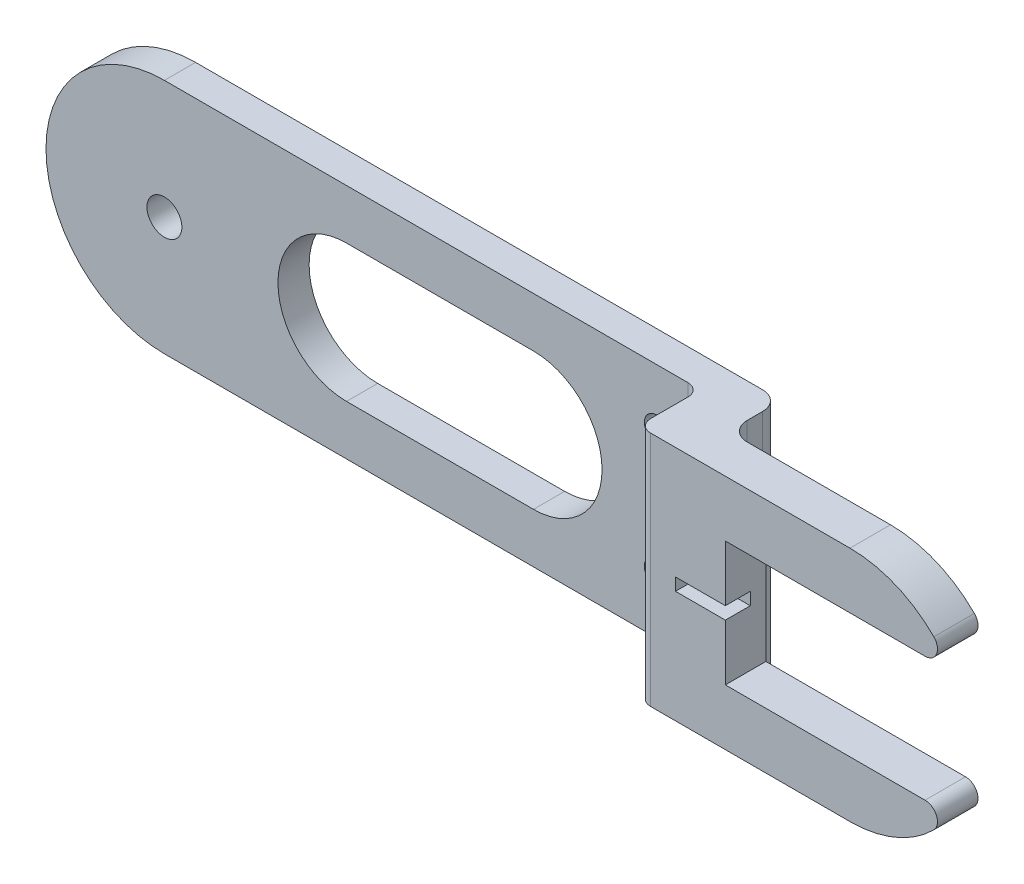
SolidWorks part; units mm, degrees
ref_plane "Front Plane" through (0, 0, 0) normal (0, 0, 1) x (1, 0, 0)
ref_plane "Top Plane" through (0, 0, 0) normal (0, 1, 0) x (1, 0, 0)
ref_plane "Right Plane" through (0, 0, 0) normal (1, 0, 0) x (0, 0, -1)
sketch "Sketch1" plane through (0, 0, 0) normal (0, 0, 1) x (1, 0, 0)
  line L0 (0, 0) -> (120, 0) construction
  line L1 (0, 19) -> (120, 19)
  line L2 (0, -19) -> (120, -19)
  line L3 (29.2177, 0) -> (59.2177, 0) construction
  line L4 (29.2177, 11) -> (59.2177, 11)
  line L5 (29.2177, -11) -> (59.2177, -11)
  line L7 (100, -10) -> (136.1555, -10)
  line L8 (100, -10) -> (100, 10)
  line L9 (100, 10) -> (136.1555, 10)
  line L11 (100, -10) -> (140, 10) construction
  line L12 (100, 10) -> (140, -10) construction
  circle A0 centre (0, 0) radius 2.8
  arc A1 (0, 19) -> (0, -19) centre (0, 0) ccw
  arc A2 (120, -19) -> (136.1555, -10) centre (120, 0) ccw
  arc A3 (29.2177, 11) -> (29.2177, -11) centre (29.2177, 0) ccw
  arc A4 (59.2177, -11) -> (59.2177, 11) centre (59.2177, 0) ccw
  arc A5 (136.1555, 10) -> (120, 19) centre (120, 0) ccw
  point P8 (44.2177, 0)
  point P17 (120, 0)
  dimension "D1" = 38
  dimension "D2" = 5.6
  dimension "D4" = 38
  dimension "D3" = 120
  dimension "D5" = 30
  dimension "D6" = 8
  dimension "D7" = 20
  dimension "D8" = 40
extrude "Boss-Extrude1" add sketch "Sketch1" along normal blind 5
fillet "Fillet1" radius 2 2 edges at (136.1555, 10, 2.5) (136.1555, -10, 2.5)
sketch "Sketch2" plane through (0, 0, 5) normal (0, 0, 1) x (1, 0, 0)
  line L0 (86, 19) -> (86, -19)
  line L1 (120, 19) -> (0, 19) construction
  line L2 (0, -19) -> (120, -19) construction
  line L3 (100, -10) -> (100, 10) construction
  line L4 (120, 19) -> (86, 19)
  line L6 (86, -19) -> (120, -19)
  line L7 (132.0416, -10) -> (100, -10) construction
  line L8 (132.0416, -10) -> (100, -10)
  line L9 (100, -10) -> (100, 10)
  line L10 (100, 10) -> (132.0416, 10) construction
  line L11 (100, 10) -> (132.0416, 10)
  arc A0 (133.4583, 13.4118) -> (120, 19) centre (120, 0) ccw construction
  arc A1 (133.4583, 13.4118) -> (120, 19) centre (120, 0) ccw
  arc A2 (120, -19) -> (133.4583, -13.4118) centre (120, 0) ccw construction
  arc A3 (120, -19) -> (133.4583, -13.4118) centre (120, 0) ccw
  arc A4 (133.4583, -13.4118) -> (132.0416, -10) centre (132.0416, -12) ccw construction
  arc A5 (133.4583, -13.4118) -> (132.0416, -10) centre (132.0416, -12) ccw
  arc A6 (132.0416, 10) -> (133.4583, 13.4118) centre (132.0416, 12) ccw construction
  arc A7 (132.0416, 10) -> (133.4583, 13.4118) centre (132.0416, 12) ccw
  point P8 (100, 0)
  dimension "D1" = 14
extrude "Boss-Extrude2" add sketch "Sketch2" along normal blind 10
fillet "Fillet2" radius 2 2 edges at (86, 0, 15) (86, 0, 5)
sketch "Sketch3" plane through (0, 0, 15) normal (0, 0, 1) x (1, 0, 0)
  line L0 (100, 0) -> (88, 0) construction
  line L1 (100, -10) -> (100, 10) construction
  line L2 (88, 19) -> (88, -19) construction
  line L3 (100, 1) -> (92, 1)
  line L4 (100, -1) -> (92, -1)
  line L5 (100, 1) -> (100, -1)
  line L6 (92, 1) -> (92, -1)
  line L8 (100, 1) -> (88, 1) construction
  line L9 (100, -1) -> (88, -1) construction
  dimension "D3" = 4
  dimension "D1" = 1
  dimension "D2" = 1
extrude "Cut-Extrude1" cut sketch "Sketch3" against normal blind 4
sketch "Sketch5" plane through (0, 0, 5) normal (0, 0, 1) x (1, 0, 0)
  line L0 (84, 19) -> (0, 19) construction
  line L1 (84, -19) -> (84, 19) construction
  circle A0 centre (79, 10) radius 2
  circle A1 centre (79, -10) radius 2
  dimension "D1" = 20
  dimension "D3" = 4
  dimension "D2" = 9
  dimension "D4" = 5
extrude "Cut-Extrude2" cut sketch "Sketch5" against normal blind 5
sketch "Sketch6" plane through (0, 0, 0) normal (0, 0, -1) x (-1, 0, 0)
  line L0 (-94, -19) -> (-94, 19)
  line L1 (0, -19) -> (-120, -19) construction
  line L2 (-120, 19) -> (0, 19) construction
  line L3 (-94, -19) -> (-183.2299, -19)
  line L4 (-183.2299, -19) -> (-183.2299, 19)
  line L5 (-183.2299, 19) -> (-94, 19)
  dimension "D1" = 8
extrude "Cut-Extrude3" cut sketch "Sketch6" against normal blind 8.5
fillet "Fillet3" radius 3 2 edges at (94, 0, 8.5) (94, 0, 0)
